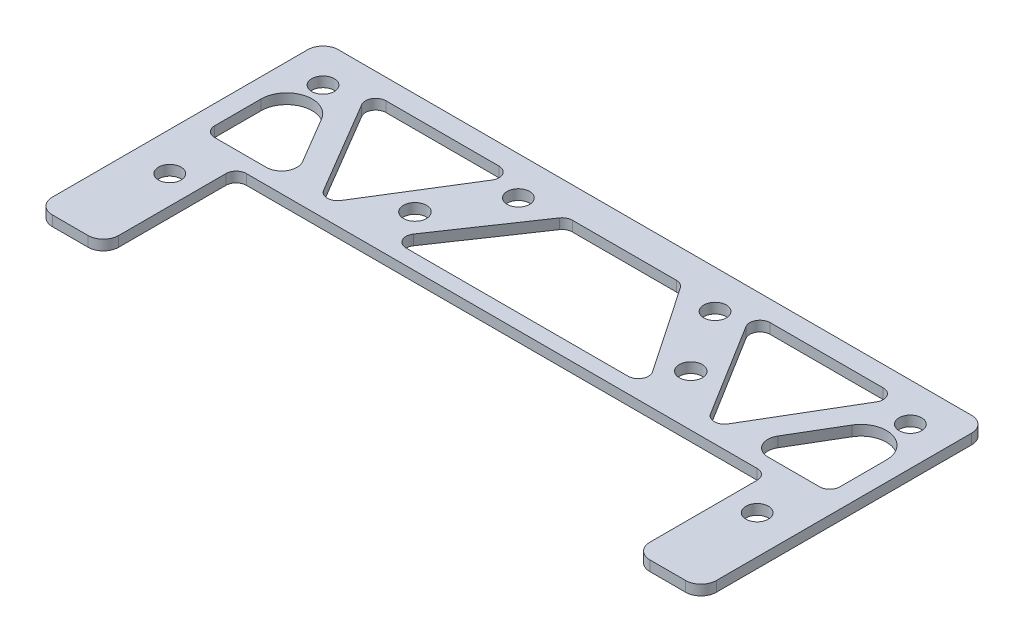
SolidWorks part; units mm, degrees
ref_plane "前视基准面" through (0, 0, 0) normal (0, 0, 1) x (1, 0, 0)
ref_plane "上视基准面" through (0, 0, 0) normal (0, 1, 0) x (1, 0, 0)
ref_plane "右视基准面" through (0, 0, 0) normal (1, 0, 0) x (0, 0, -1)
other "Configuration Table"
sketch "草图1" plane through (0, 0, 0) normal (0, 1, 0) x (1, 0, 0)
  line L0 (13, 0) -> (13, -56)
  line L1 (0, 0) -> (130, 0)
  line L2 (0, 0) -> (0, -56)
  line L3 (0, -56) -> (130, -56)
  line L4 (130, 0) -> (130, -56)
  line L5 (117, 0) -> (117, -56)
  line L6 (65, 0) -> (65, -56) construction
  line L7 (0, -15) -> (130, -15)
  line L8 (0, -7.5) -> (130, -7.5) construction
  line L9 (7.5, 0) -> (7.5, -56) construction
  line L10 (122.5, 0) -> (122.5, -56) construction
  line L11 (0, -34) -> (130, -34)
  circle A0 centre (7.5, -7.5) radius 2.2
  circle A1 centre (7.5, -37.5) radius 2.2
  circle A2 centre (45.75, -7.5) radius 2.2
  circle A3 centre (84.25, -7.5) radius 2.2
  circle A4 centre (122.5, -37.5) radius 2.2
  circle A5 centre (122.5, -7.5) radius 2.2
  dimension "D9" = 30
  dimension "D10" = 4.4
  dimension "D11" = 38.5
  dimension "D1" = 130
  dimension "D2" = 56
  dimension "D3" = 13
  dimension "D4" = 15
  dimension "D5" = 7.5
  dimension "D6" = 7.5
  dimension "D7" = 7.5
  dimension "D8" = 34
extrude "凸台-拉伸3" add sketch "草图1" along normal blind 2 contours L11 L2 L3 L0 A1 | L2 L11 L0 L7 | L2 L7 L0 L1 A0 | L0 L7 L5 L1 A3 A2 | L5 L7 L4 L1 A5 | L5 L11 L4 L7 | L11 L5 L3 L4 A4 | L0 L11 L5 L7
sketch "草图2" plane through (0, 2, 0) normal (0, 1, 0) x (1, 0, 0)
  line L0 (65, 0) -> (65, -34) construction
  line L1 (0, -20) -> (130, -20) construction
  line L8 (130, 0) -> (0, 0)
  line L9 (0, 0) -> (0, -56)
  line L10 (0, -56) -> (13, -56)
  line L11 (13, -56) -> (13, -34)
  line L12 (13, -34) -> (117, -34)
  line L13 (117, -34) -> (117, -56)
  line L14 (0, -56) -> (13, -56)
  line L15 (130, -56) -> (130, 0)
  line L16 (130, 0) -> (0, 0)
  line L17 (0, 0) -> (0, -56)
  line L19 (13, -56) -> (13, -34)
  line L20 (13, -34) -> (117, -34)
  line L21 (117, -34) -> (117, -56)
  line L23 (130, -56) -> (130, 0)
  line L26 (117, -56) -> (130, -56)
  line L27 (117, -56) -> (130, -56)
  circle A0 centre (38, -20) radius 2.25
  circle A1 centre (92, -20) radius 2.25
  dimension "D3" = 4.5
  dimension "D4" = 54
  dimension "D2" = 20
  dimension "D1" = 0
extrude "切除-拉伸1" cut sketch "草图2" against normal blind 10 contours A0 | A1
sketch "草图3" plane through (0, 2, 0) normal (0, 1, 0) x (1, 0, 0)
  line L0 (16.3202, -4) -> (38.4438, -4)
  line L1 (40.1436, -7.0539) -> (28.8171, -25.3223)
  line L2 (25.3956, -25.2861) -> (14.5984, -7.0176)
  line L3 (45.75, -7.5) -> (38, -20)
  line L4 (18.4779, -22.4736) -> (13.0932, -13.3627)
  line L5 (3.7887, -15.9067) -> (3.7887, -25)
  line L6 (5.7887, -27) -> (15.8953, -27)
  line L7 (65, 0) -> (65, -34) construction
  line L8 (130, 0) -> (0, 0)
  line L9 (0, 0) -> (0, -56)
  line L10 (0, -56) -> (13, -56)
  line L11 (13, -56) -> (13, -34)
  line L12 (13, -34) -> (117, -34)
  line L13 (117, -34) -> (117, -56)
  line L14 (0, -56) -> (13, -56)
  line L15 (130, -56) -> (130, 0)
  line L16 (130, 0) -> (0, 0)
  line L17 (0, 0) -> (0, -56)
  line L19 (13, -56) -> (13, -34)
  line L20 (13, -34) -> (117, -34)
  line L21 (117, -34) -> (117, -56)
  line L23 (130, -56) -> (130, 0)
  line L24 (126.2113, -15.9067) -> (126.2113, -25)
  line L25 (111.5221, -22.4736) -> (116.9068, -13.3627)
  line L26 (124.2113, -27) -> (114.1047, -27)
  line L27 (89.8564, -7.0539) -> (101.1829, -25.3223)
  line L28 (113.6798, -4) -> (91.5562, -4)
  line L29 (104.6044, -25.2861) -> (115.4016, -7.0176)
  line L30 (54.8098, -6) -> (75.1902, -6)
  line L31 (76.8451, -6.877) -> (88.3808, -23.877)
  line L32 (86.7259, -27) -> (43.2741, -27)
  line L33 (41.6192, -23.877) -> (53.1549, -6.877)
  line L42 (117, -56) -> (130, -56)
  line L43 (117, -56) -> (130, -56)
  circle A0 centre (7.5, -7.5) radius 2.2 construction
  circle A1 centre (7.5, -7.5) radius 2.2
  circle A2 centre (122.5, -7.5) radius 2.2 construction
  circle A3 centre (92, -20) radius 2.25 construction
  circle A4 centre (84.25, -7.5) radius 2.2 construction
  circle A5 centre (38, -20) radius 2.25 construction
  circle A6 centre (45.75, -7.5) radius 2.2 construction
  circle A7 centre (122.5, -7.5) radius 2.2
  circle A24 centre (92, -20) radius 2.25
  circle A25 centre (84.25, -7.5) radius 2.2
  circle A26 centre (38, -20) radius 2.25
  circle A27 centre (45.75, -7.5) radius 2.2
  arc A28 (13.0932, -13.3627) -> (3.7887, -15.9067) centre (8.7887, -15.9067) ccw
  arc A29 (18.4779, -22.4736) -> (15.8953, -27) centre (15.8953, -24) cw
  arc A30 (3.7887, -25) -> (5.7887, -27) centre (5.7887, -25) ccw
  arc A31 (16.3202, -4) -> (14.5984, -7.0176) centre (16.3202, -6) ccw
  arc A32 (28.8171, -25.3223) -> (25.3956, -25.2861) centre (27.1173, -24.2684) cw
  arc A33 (38.4438, -4) -> (40.1436, -7.0539) centre (38.4438, -6) cw
  arc A34 (116.9068, -13.3627) -> (126.2113, -15.9067) centre (121.2113, -15.9067) cw
  arc A35 (111.5221, -22.4736) -> (114.1047, -27) centre (114.1047, -24) ccw
  arc A36 (126.2113, -25) -> (124.2113, -27) centre (124.2113, -25) cw
  arc A37 (91.5562, -4) -> (89.8564, -7.0539) centre (91.5562, -6) ccw
  arc A38 (113.6798, -4) -> (115.4016, -7.0176) centre (113.6798, -6) cw
  arc A39 (101.1829, -25.3223) -> (104.6044, -25.2861) centre (102.8827, -24.2684) ccw
  arc A40 (75.1902, -6) -> (76.8451, -6.877) centre (75.1902, -8) cw
  arc A41 (88.3808, -23.877) -> (86.7259, -27) centre (86.7259, -25) cw
  arc A42 (43.2741, -27) -> (41.6192, -23.877) centre (43.2741, -25) cw
  arc A43 (54.8098, -6) -> (53.1549, -6.877) centre (54.8098, -8) ccw
  point P5 (0, 0)
  point P8 (10.3069, -18.262)
  point P9 (10.3069, -16.0095)
  point P10 (15.8953, -25.2861)
  point P11 (0, 0)
  point P89 (76.25, -6)
  point P92 (90.5, -27)
  point P95 (39.5, -27)
  point P98 (53.75, -6)
  dimension "D5" = 5
  dimension "D6" = 3
  dimension "D7" = 2
  dimension "D8" = 2
  dimension "D9" = 2
  dimension "D10" = 2
  dimension "D14" = 2
  dimension "D2" = 5
  dimension "D3" = 4
  dimension "D4" = 7
  dimension "D11" = 7
  dimension "D12" = 22.5
  dimension "D13" = 51
  dimension "D1" = 0
extrude "切除-拉伸2" cut sketch "草图3" against normal blind 10 contours A33 L0 A31 L2 A32 L1 | L5 A30 L6 A29 L4 A28 | L7 L30 A43 L33 A42 L32 | L30 L7 L32 A41 L31 A40 | L27 A39 L29 A38 L28 A37 | A36 L24 A34 L25 A35 L26
sketch "草图4" plane through (0, 2, 0) normal (0, 1, 0) x (1, 0, 0)
  line L0 (13, -34) -> (117, -34) construction
  line L1 (13, -34) -> (117, -34)
  line L2 (13, -34) -> (13, -30)
  line L3 (13, -30) -> (117, -30)
  line L4 (117, -30) -> (117, -34)
  dimension "D1" = 4
extrude "切除-拉伸3" cut sketch "草图4" against normal blind 10
fillet "圆角1" radius 2 2 edges at (117, 1, 30) (13, 1, 30)
fillet "圆角2" radius 3 6 edges at (0, 1, 0) (130, 1, 0) (117, 1, 56) (130, 1, 56) (0, 1, 56) (13, 1, 56)
